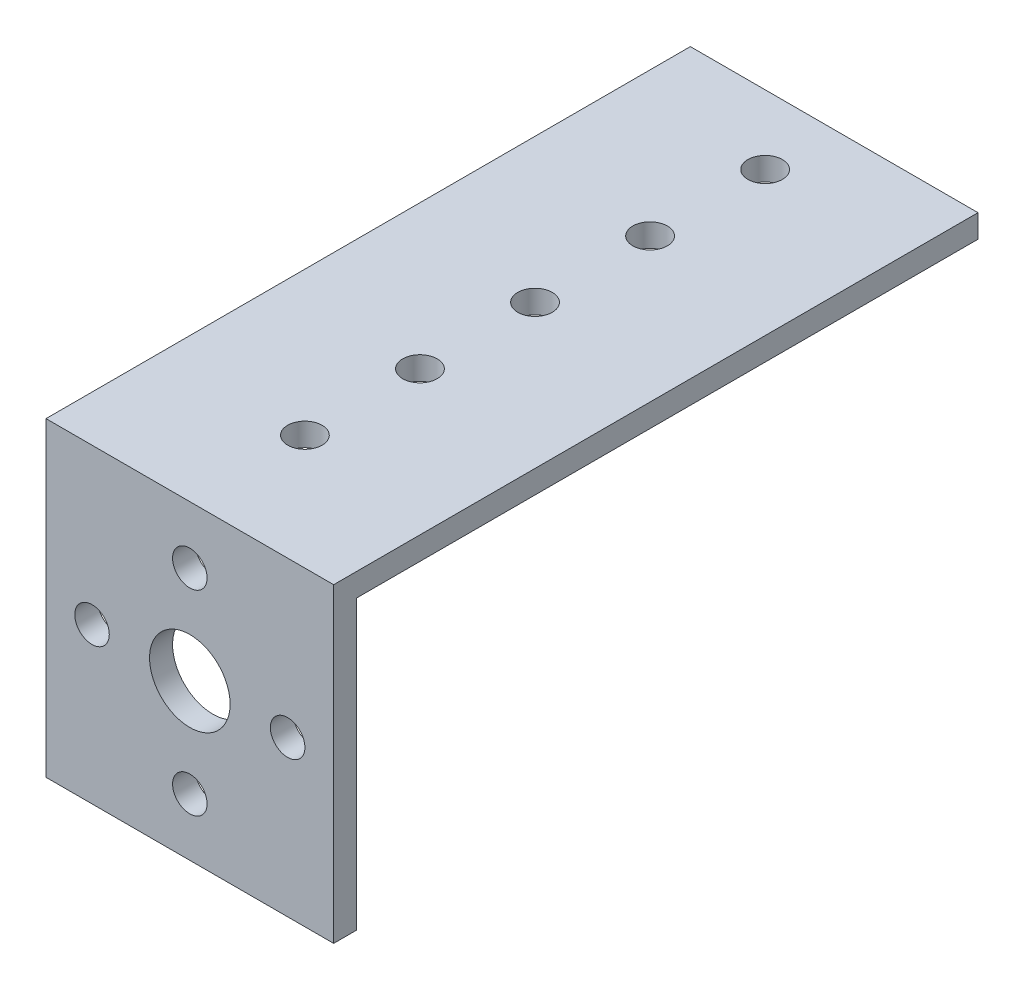
SolidWorks part; units mm, degrees
ref_plane "Front Plane" through (0, 0, 0) normal (0, 0, 1) x (1, 0, 0)
ref_plane "Top Plane" through (0, 0, 0) normal (0, 1, 0) x (1, 0, 0)
ref_plane "Right Plane" through (0, 0, 0) normal (1, 0, 0) x (0, 0, -1)
sketch "Sketch1" plane through (0, 0, 0) normal (1, 0, 0) x (0, 0, -1)
  line L0 (0, 0) -> (0, 27)
  line L1 (0, 27) -> (56, 27)
  line L2 (56, 27) -> (56, 25)
  line L3 (56, 25) -> (2, 25)
  line L4 (2, 25) -> (2, 0)
  line L5 (2, 0) -> (0, 0)
  point P3 (0, 27)
  point P8 (0, 27)
  point P9 (55.3079, 26.8764)
  dimension "D1" = 25
  dimension "D2" = 2
  dimension "D3" = 54
extrude "Boss-Extrude1" add sketch "Sketch1" along normal blind 25
sketch "Sketch2" plane through (0, 0, 0) normal (0, 0, 1) x (1, 0, 0)
  line L0 (12.5, 27) -> (12.5, 0) construction
  line L1 (25, 13.5) -> (0, 13.5) construction
  line L4 (0, 27) -> (0, 0)
  line L5 (0, 0) -> (25, 0)
  line L6 (25, 0) -> (25, 27)
  line L7 (25, 27) -> (0, 27)
  line L8 (0, 27) -> (0, 0) construction
  line L9 (0, 0) -> (25, 0) construction
  line L10 (25, 0) -> (25, 27) construction
  line L11 (25, 27) -> (0, 27) construction
  circle A3 centre (4, 13.5) radius 1.5
  circle A4 centre (12.5, 13.5) radius 3.5
  circle A5 centre (12.5, 22) radius 1.5
  circle A6 centre (21, 13.5) radius 1.5
  circle A7 centre (12.5, 5) radius 1.5
  point P8 (12.5, 22.6712)
  point P9 (12.5, 5)
  point P21 (12.5, 13.5)
  dimension "D2" = 3
  dimension "D3" = 7
  dimension "D4" = 8.5
  dimension "D1" = 0
  dimension "D5" = 4
extrude "Cut-Extrude1" cut sketch "Sketch2" against normal blind 25
sketch "Sketch3" plane through (0, 27, 0) normal (0, 1, 0) x (1, 0, 0)
  line L0 (12.5, 0) -> (12.5, 56) construction
  line L1 (25, 0) -> (0, 0) construction
  line L2 (25, 56) -> (0, 56) construction
  circle A0 centre (12.5, 10) radius 1.5
  circle A1 centre (12.5, 20) radius 1.5
  circle A2 centre (12.5, 30) radius 1.5
  circle A3 centre (12.5, 40) radius 1.5
  circle A4 centre (12.5, 50) radius 1.5
  point P9 (12.5, 12.9678)
  point P17 (12.5, 7.9808)
  point P18 (12.5, 17.5273)
  dimension "D1" = 3
  dimension "D3" = 10
  dimension "D4" = 10
  dimension "D2" = 5
extrude "Cut-Extrude2" cut sketch "Sketch3" against normal blind 25
